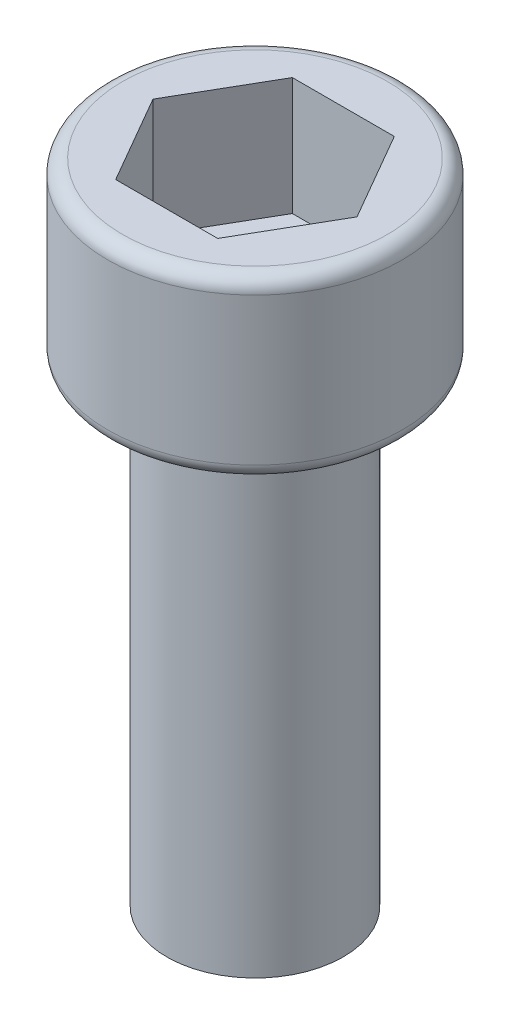
SolidWorks part; units mm, degrees
material "Galvanized Steel"
ref_plane "Front Plane" through (0, 0, 0) normal (0, 0, 1) x (1, 0, 0)
ref_plane "Top Plane" through (0, 0, 0) normal (0, 1, 0) x (1, 0, 0)
ref_plane "Right Plane" through (0, 0, 0) normal (1, 0, 0) x (0, 0, -1)
sketch "Sketch1" plane through (0, 0, 0) normal (0, 0, 1) x (1, 0, 0)
  line L0 (0, -5.5) -> (1.5, -5.5)
  line L1 (1.5, -5.5) -> (1.5, 2.5)
  line L2 (1.5, 2.5) -> (2.5, 2.5)
  line L3 (2.5, 2.5) -> (2.5, 5.5)
  line L4 (2.5, 5.5) -> (0, 5.5)
  line L5 (0, 5.5) -> (0, -5.5)
  line L6 (0, -1000) -> (0, 49000) construction
  point P2 (0, 0)
  dimension "D1" = 3
  dimension "D2" = 5
  dimension "D3" = 3
  dimension "D4" = 8
revolve "Revolve1" add sketch "Sketch1" angle 360 about L6
sketch "Sketch2" plane through (0, 5.5, 0) normal (0, 1, 0) x (1, 0, 0)
  line L1 (0.866, 1.5) -> (-0.866, 1.5)
  line L2 (-0.866, 1.5) -> (-1.7321, 0)
  line L3 (-1.7321, 0) -> (-0.866, -1.5)
  line L4 (-0.866, -1.5) -> (0.866, -1.5)
  line L5 (0.866, -1.5) -> (1.7321, 0)
  line L6 (1.7321, 0) -> (0.866, 1.5)
  circle A0 centre (0, 0) radius 1.5 construction
  dimension "D1" = 3
extrude "Cut-Extrude1" cut sketch "Sketch2" against normal blind 2
fillet "Fillet1" radius 0.25 2 edges at (2.5, 2.5, 0) (2.5, 5.5, 0)
